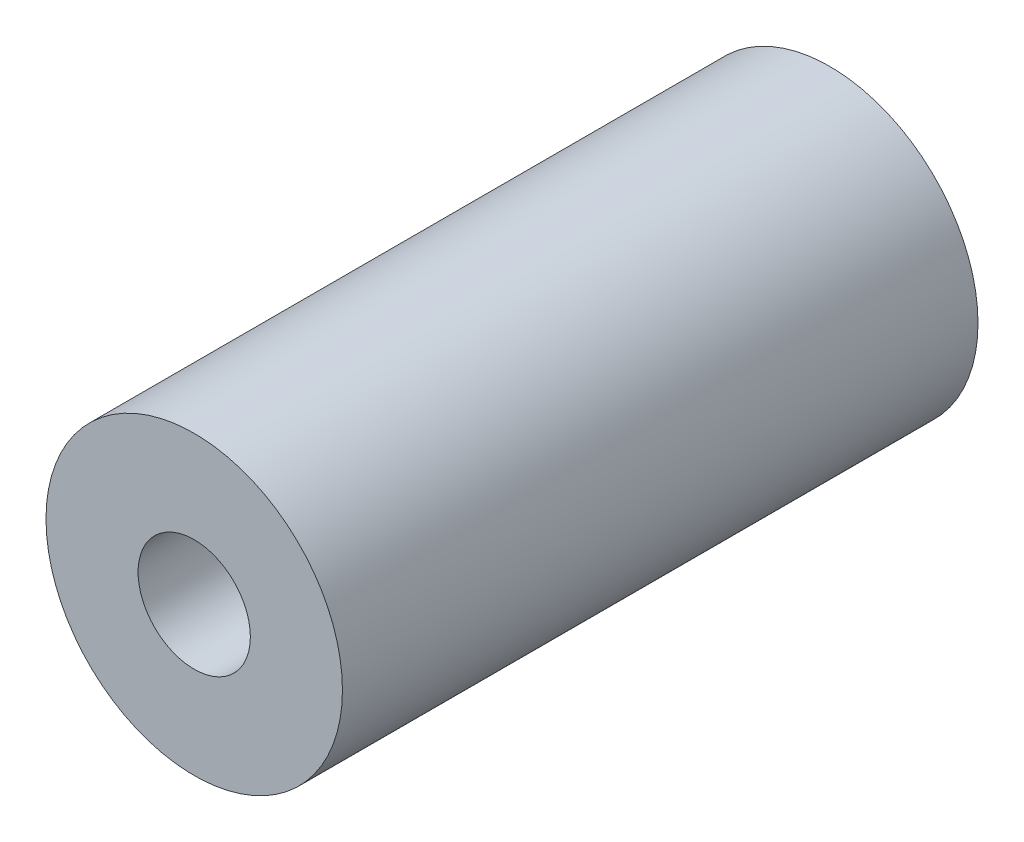
SolidWorks part; units mm, degrees
ref_plane "Front Plane" through (0, 0, 0) normal (0, 0, 1) x (1, 0, 0)
ref_plane "Top Plane" through (0, 0, 0) normal (0, 1, 0) x (1, 0, 0)
ref_plane "Right Plane" through (0, 0, 0) normal (1, 0, 0) x (0, 0, -1)
sketch "Sketch2" plane through (0, 0, 0) normal (0, 0, 1) x (1, 0, 0)
  circle A0 centre (0, 0) radius 6.6
  circle A1 centre (0, 0) radius 2.5
  dimension "D1" = 13.2
  dimension "D2" = 5
extrude "Boss-Extrude1" add sketch "Sketch2" against normal blind 28.3
